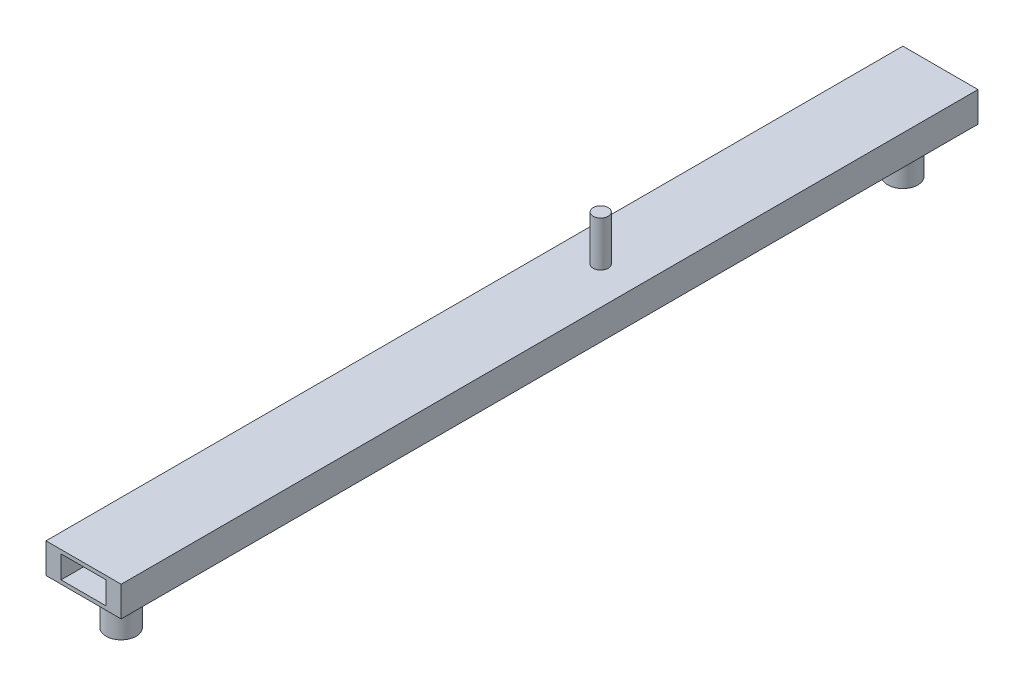
SolidWorks part; units mm, degrees
ref_plane "Спереди" through (0, 0, 0) normal (0, 0, 1) x (1, 0, 0)
ref_plane "Сверху" through (0, 0, 0) normal (0, 1, 0) x (1, 0, 0)
ref_plane "Справа" through (0, 0, 0) normal (1, 0, 0) x (0, 0, -1)
sketch "Эскиз1" plane through (0, 0, 0) normal (0, 0, 1) x (1, 0, 0)
  line L1 (-25, -10) -> (25, -10)
  line L2 (-25, -10) -> (-25, 10)
  line L3 (-25, 10) -> (25, 10)
  line L4 (25, -10) -> (25, 10)
  line L5 (-25, -10) -> (25, 10) construction
  line L6 (-25, 10) -> (25, -10) construction
  line L7 (-15, -7.5) -> (15, -7.5)
  line L8 (-15, -7.5) -> (-15, 7.5)
  line L9 (-15, 7.5) -> (15, 7.5)
  line L10 (15, -7.5) -> (15, 7.5)
  line L11 (-15, -7.5) -> (15, 7.5) construction
  line L12 (-15, 7.5) -> (15, -7.5) construction
  point P0 (0, 0)
  point P6 (0, 0)
  dimension "D1" = 50
  dimension "D2" = 20
  dimension "D3" = 30
  dimension "D4" = 15
extrude "Бобышка-Вытянуть1" add sketch "Эскиз1" along normal mid plane 570
sketch "Эскиз2" plane through (0, -10, 0) normal (0, -1, 0) x (1, 0, 0)
  line L0 (-25, 285) -> (25, 285) construction
  line L1 (25, 285) -> (25, -285) construction
  line L3 (0, 0) -> (55.2179, 0) construction
  circle A0 centre (0, 260) radius 10
  circle A1 centre (0, -260) radius 10
  dimension "D1" = 20
  dimension "D2" = 25
  dimension "D3" = 25
extrude "Бобышка-Вытянуть2" add sketch "Эскиз2" along normal blind 30
sketch "Эскиз3" plane through (0, 10, 0) normal (0, 1, 0) x (1, 0, 0)
  line L0 (25, -285) -> (25, 285) construction
  circle A0 centre (0, 59) radius 5
  dimension "D1" = 10
  dimension "D2" = 59
  dimension "D3" = 25
extrude "Бобышка-Вытянуть3" add sketch "Эскиз3" along normal blind 30
